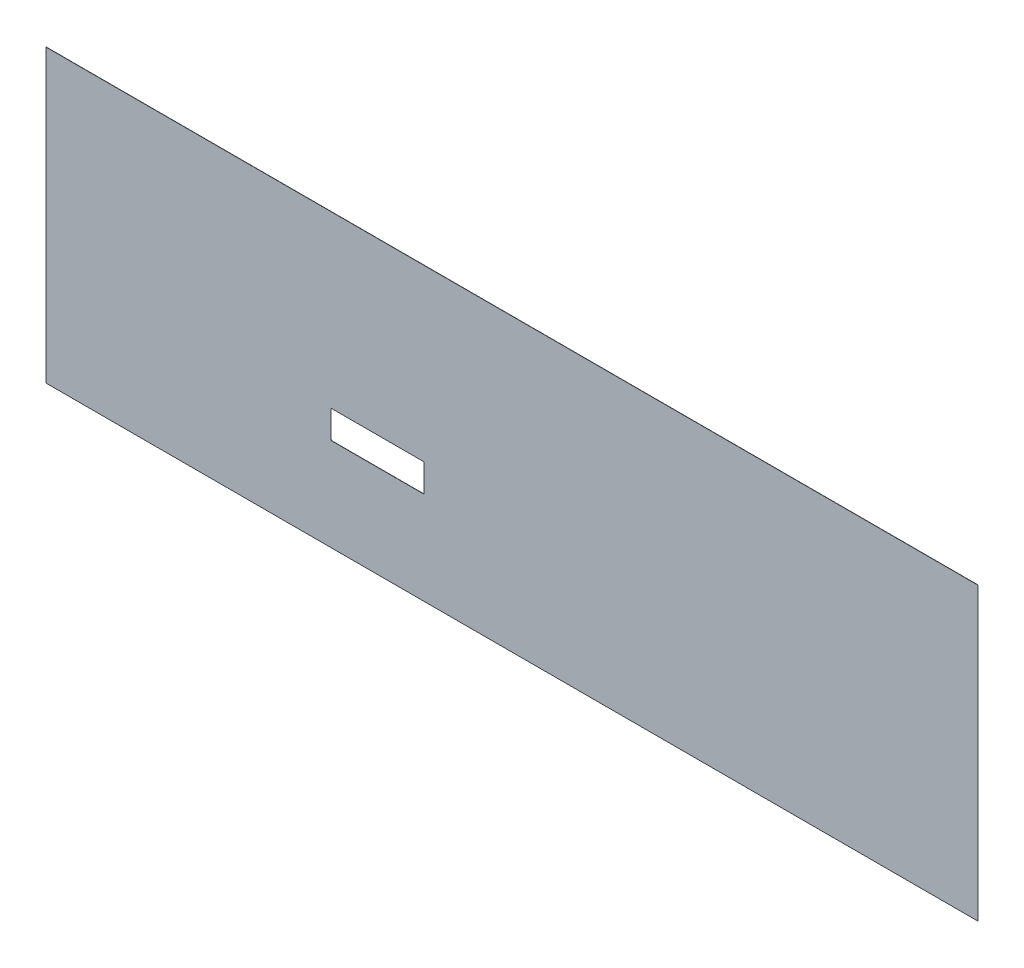
SolidWorks part; units mm, degrees
ref_plane "Front Plane" through (0, 0, 0) normal (0, 0, 1) x (1, 0, 0)
ref_plane "Top Plane" through (0, 0, 0) normal (0, 1, 0) x (1, 0, 0)
ref_plane "Right Plane" through (0, 0, 0) normal (1, 0, 0) x (0, 0, -1)
sketch "Sketch2" plane through (0, 0, -8280.4) normal (0, 0, 1) x (1, 0, 0)
  line L4 (-819.15, 1987.5817) -> (-863.6, 1987.5817)
  line L5 (-863.6, 1987.5817) -> (-863.6, 6.3817)
  line L6 (-863.6, 6.3817) -> (-819.15, 6.3817)
  line L7 (-819.15, 6.3817) -> (-819.15, 1987.5817)
  line L8 (-819.15, 1987.5817) -> (-863.6, 1987.5817)
  line L9 (-863.6, 1987.5817) -> (-863.6, 6.3817)
  line L10 (-863.6, 6.3817) -> (-819.15, 6.3817)
  line L11 (-819.15, 6.3817) -> (-819.15, 1987.5817)
  line L12 (5480.05, 1987.5817) -> (5435.6, 1987.5817)
  line L13 (5435.6, 1987.5817) -> (5435.6, 6.3817)
  line L14 (5435.6, 6.3817) -> (5480.05, 6.3817)
  line L15 (5480.05, 6.3817) -> (5480.05, 1987.5817)
  line L16 (5480.05, 1987.5817) -> (5435.6, 1987.5817)
  line L17 (5435.6, 1987.5817) -> (5435.6, 6.3817)
  line L18 (5435.6, 6.3817) -> (5480.05, 6.3817)
  line L19 (5480.05, 6.3817) -> (5480.05, 1987.5817)
  line L20 (1012.825, 1984.4067) -> (1012.825, 3.2068)
  line L21 (1012.825, 3.2068) -> (1774.825, 3.2068)
  line L22 (1774.825, 3.2068) -> (1774.825, 1984.4067)
  line L23 (1774.825, 1984.4067) -> (1012.825, 1984.4067)
  line L24 (1012.825, 1984.4067) -> (1012.825, 3.2068)
  line L25 (1012.825, 3.2068) -> (1774.825, 3.2068)
  line L26 (1774.825, 3.2068) -> (1774.825, 1984.4067)
  line L27 (1774.825, 1984.4067) -> (1012.825, 1984.4067)
  line L29 (-863.6, 1987.5817) -> (5480.05, 1987.5817)
  line L30 (-863.6, 1987.5817) -> (-863.6, 6.3817)
  line L31 (-863.6, 6.3817) -> (5480.05, 6.3817)
  line L32 (1711.325, 644.5567) -> (1711.325, 822.3567)
  line L33 (1082.675, 638.2068) -> (1704.975, 638.2067)
  line L34 (1076.325, 822.3567) -> (1076.325, 644.5567)
  line L35 (1704.975, 828.7067) -> (1082.675, 828.7067)
  line L36 (1711.325, 644.5567) -> (1711.325, 822.3567)
  line L37 (1082.675, 638.2068) -> (1704.975, 638.2067)
  line L38 (1076.325, 822.3567) -> (1076.325, 644.5567)
  line L39 (1704.975, 828.7067) -> (1082.675, 828.7067)
  line L40 (5480.05, 1987.5817) -> (5480.05, 6.3817)
  arc A4 (1711.325, 822.3567) -> (1704.975, 828.7067) centre (1704.975, 822.3567) ccw
  arc A5 (1704.975, 638.2067) -> (1711.325, 644.5567) centre (1704.975, 644.5567) ccw
  arc A6 (1076.325, 644.5567) -> (1082.675, 638.2068) centre (1082.675, 644.5567) ccw
  arc A7 (1082.675, 828.7067) -> (1076.325, 822.3567) centre (1082.675, 822.3567) ccw
  arc A8 (1711.325, 822.3567) -> (1704.975, 828.7067) centre (1704.975, 822.3567) ccw
  arc A9 (1704.975, 638.2067) -> (1711.325, 644.5567) centre (1704.975, 644.5567) ccw
  arc A10 (1076.325, 644.5567) -> (1082.675, 638.2068) centre (1082.675, 644.5567) ccw
  arc A11 (1082.675, 828.7067) -> (1076.325, 822.3567) centre (1082.675, 822.3567) ccw
  dimension "D1" = 0
  dimension "D2" = 0
  dimension "D3" = 0
  dimension "D4" = 0
extrude "Boss-Extrude1" add sketch "Sketch2" against normal up to surface (1.5875 mm away)
